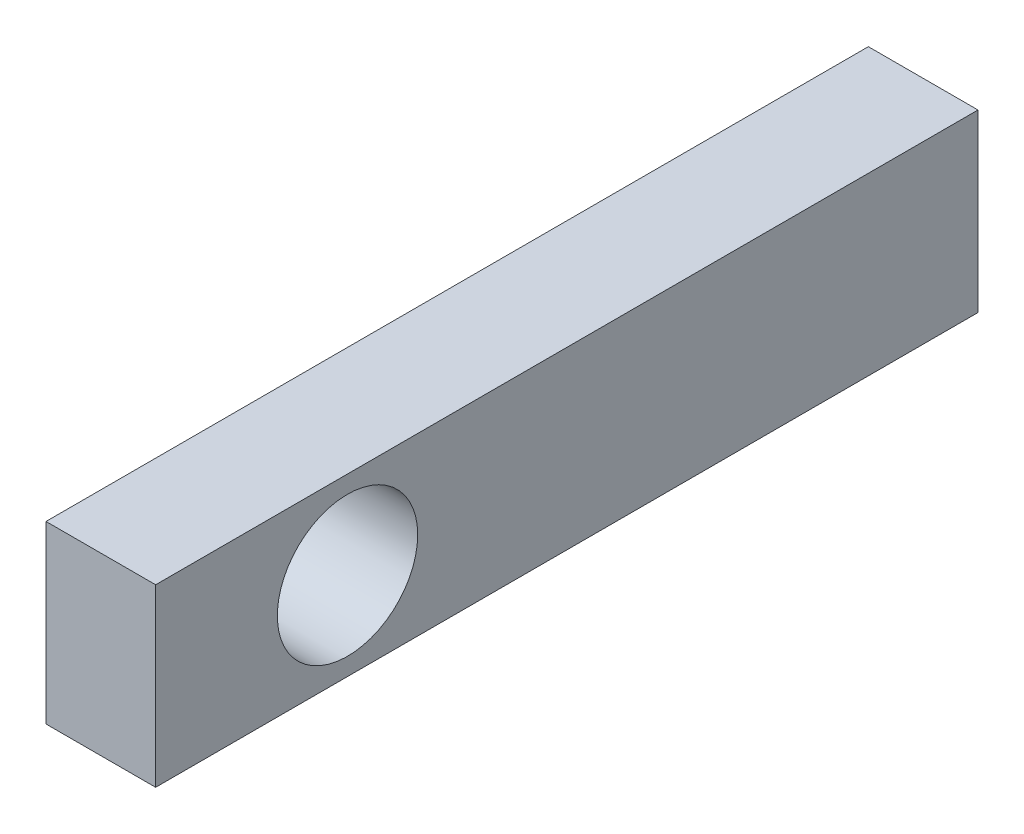
SolidWorks part; units mm, degrees
ref_plane "Front Plane" through (0, 0, 0) normal (0, 0, 1) x (1, 0, 0)
ref_plane "Top Plane" through (0, 0, 0) normal (0, 1, 0) x (1, 0, 0)
ref_plane "Right Plane" through (0, 0, 0) normal (1, 0, 0) x (0, 0, -1)
sketch "Sketch1" plane through (0, 0, 0) normal (0, 0, 1) x (1, 0, 0)
  line L0 (0, 77.6) -> (4, 77.6)
  line L1 (4, 77.6) -> (4, 84)
  line L2 (4, 84) -> (0, 84)
  line L3 (0, 84) -> (0, 77.6)
extrude "Base-mounted stop block" add sketch "Sketch1" along normal blind 30 from offset 27
sketch "Sketch2" plane through (0, 0, 0) normal (1, 0, 0) x (0, 0, -1)
  circle A0 centre (-50, 80.8) radius 2.56
extrude "M6 tap core" cut sketch "Sketch2" along normal blind 4
